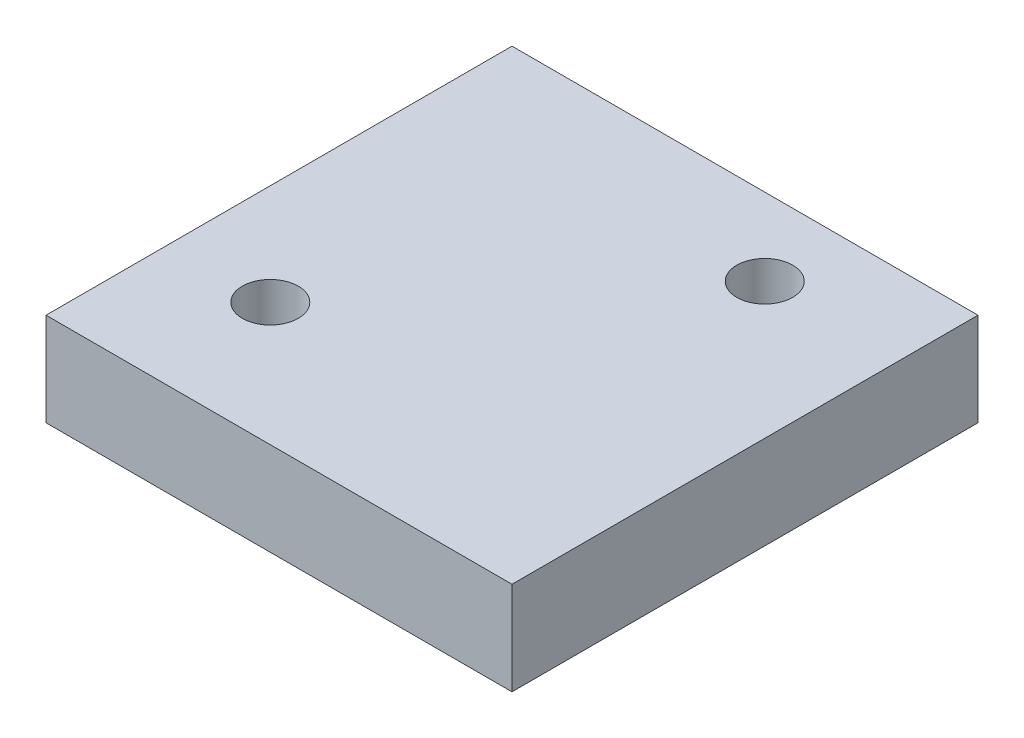
SolidWorks part; units mm, degrees
ref_plane "Front Plane" through (0, 0, 0) normal (0, 0, 1) x (1, 0, 0)
ref_plane "Top Plane" through (0, 0, 0) normal (0, 1, 0) x (1, 0, 0)
ref_plane "Right Plane" through (0, 0, 0) normal (1, 0, 0) x (0, 0, -1)
sketch "Sketch1" plane through (0, 0, 0) normal (0, 1, 0) x (1, 0, 0)
  line L1 (0, 0) -> (100, 0)
  line L2 (0, 0) -> (0, 100)
  line L3 (0, 100) -> (100, 100)
  line L4 (100, 0) -> (100, 100)
  dimension "D1" = 100
  dimension "D2" = 100
extrude "Boss-Extrude1" add sketch "Sketch1" along normal blind 20
hole_wizard "Ø12.0 (12) Diameter Hole1" positions "Sketch2" profile "Sketch3" hole size "Ø12.0" standard "ISO" end condition through all
sketch "Sketch2" plane through (0, 20, 0) normal (0, 1, 0) x (1, 0, 0)
  point P0 (21.6607, 26.4705)
  point P2 (70.8143, 83.4211)
sketch "Sketch3" plane through (21.6607, 20, -26.4705) normal (1, 0, 0) x (0, 0, 1)
  line L0 (0, 0) -> (0, 20)
  line L1 (0, 20) -> (6, 20)
  line L2 (6, 20) -> (6, 0)
  line L5 (6, 0) -> (0, 0)
  line L11 (0, -6.35) -> (0, 107.95) construction
  dimension "Thru Hole Dia." = 12
  dimension "Thru Hole Depth" = 20
